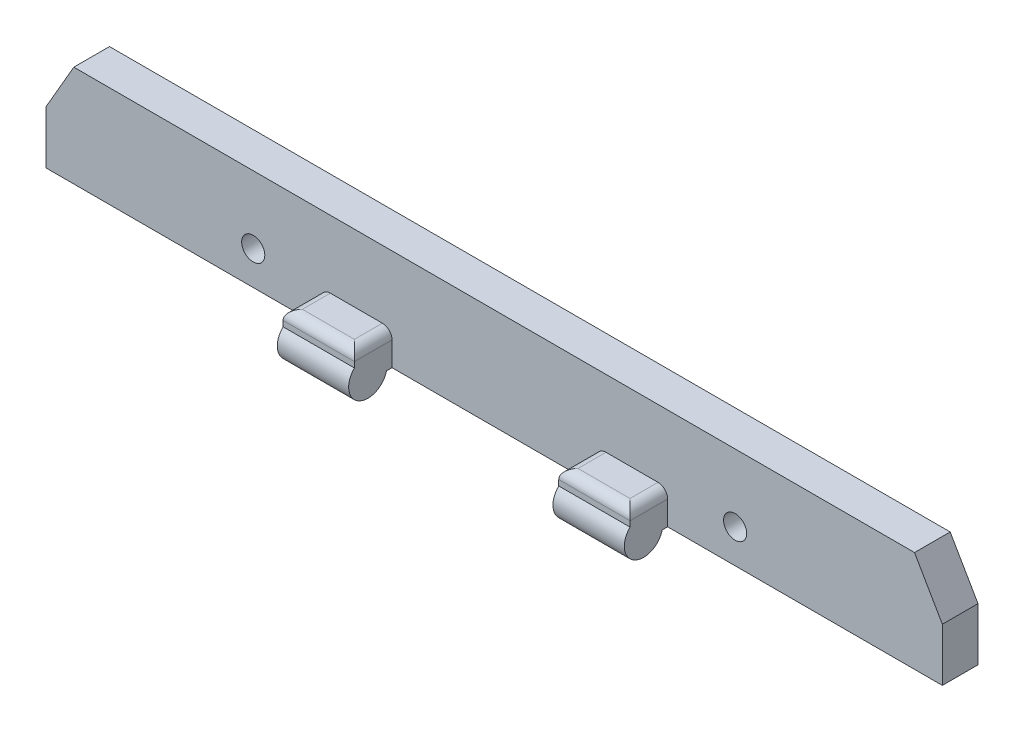
SolidWorks part; units mm, degrees
material "ABS"
ref_plane "正面" through (0, 0, 0) normal (0, 0, 1) x (1, 0, 0)
ref_plane "平面" through (0, 0, 0) normal (0, 1, 0) x (1, 0, 0)
ref_plane "右側面" through (0, 0, 0) normal (1, 0, 0) x (0, 0, -1)
sketch "ｽｹｯﾁ1" plane through (0, 0, 0) normal (0, 0, 1) x (1, 0, 0)
  line L0 (-46.5, 0) -> (46.5, 0) construction
  line L1 (46.5, -3.5) -> (-46.5, -3.5)
  line L2 (46.5, -3.5) -> (46.5, 3.5)
  line L3 (46.5, 3.5) -> (-46.5, 3.5)
  line L4 (-46.5, -3.5) -> (-46.5, 3.5)
  line L5 (46.5, -3.5) -> (-46.5, 3.5) construction
  line L6 (46.5, 3.5) -> (-46.5, -3.5) construction
  circle A0 centre (-25, 0) radius 1.2
  circle A1 centre (25, 0) radius 1.2
  point P0 (0, 0)
  dimension "D4" = 50
  dimension "D5" = 2.4
  dimension "D6" = 2.4
  dimension "D1" = 7
  dimension "D2" = 93
  dimension "D3" = 25
extrude "ﾎﾞｽ - 押し出し1" add sketch "ｽｹｯﾁ1" along normal blind 3.7
sketch "ｽｹｯﾁ2" plane through (0, 0, 3.7) normal (0, 0, 1) x (1, 0, 0)
  line L0 (0, 3.5) -> (0, -3.5) construction
  line L1 (-10.6, -3.5) -> (-18, -3.5)
  line L2 (-10.6, -3.5) -> (-10.6, 0)
  line L3 (-10.6, 0) -> (-18, 0)
  line L4 (-18, -3.5) -> (-18, 0)
  line L5 (-10.6, -3.5) -> (-18, 0) construction
  line L6 (-10.6, 0) -> (-18, -3.5) construction
  line L7 (18, -3.5) -> (10.6, -3.5)
  line L8 (18, -3.5) -> (18, 0)
  line L9 (18, 0) -> (10.6, 0)
  line L10 (10.6, -3.5) -> (10.6, 0)
  line L11 (18, -3.5) -> (10.6, 0) construction
  line L12 (18, 0) -> (10.6, -3.5) construction
  line L13 (46.5, 3.5) -> (-46.5, 3.5) construction
  line L14 (-46.5, -3.5) -> (46.5, -3.5) construction
  line L15 (-46.5, 0) -> (46.5, 0) construction
  line L16 (-46.5, 3.5) -> (-46.5, -3.5) construction
  line L17 (46.5, -3.5) -> (46.5, 3.5) construction
  point P0 (-14.3, -1.75)
  point P5 (14.3, -1.75)
  dimension "D1" = 18
  dimension "D2" = 7.4
  dimension "D3" = 7.4
  dimension "D4" = 18
extrude "ﾎﾞｽ - 押し出し2" add sketch "ｽｹｯﾁ2" along normal blind 5
sketch "ｽｹｯﾁ3" plane through (-18, 0, 0) normal (-1, 0, 0) x (0, 0, 1)
  line L0 (6.2, 0) -> (6.2, -3.5) construction
  line L1 (4.2635, -3.5) -> (8.1365, -3.5)
  line L3 (8.7, 0) -> (3.7, 0) construction
  line L4 (8.7, -3.5) -> (3.7, -3.5) construction
  arc A0 (4.2635, -3.5) -> (8.1365, -3.5) centre (6.2, -3) ccw
  dimension "D1" = 2
  dimension "D2" = 0.5
extrude "ﾎﾞｽ - 押し出し3" add sketch "ｽｹｯﾁ3" against normal up to surface (7.4 mm away) up to face at (-10.6, -1.75, 6.2)
sketch "ｽｹｯﾁ4" plane through (18, 0, 0) normal (1, 0, 0) x (0, 0, -1)
  line L0 (-6.2, 0) -> (-6.2, -3.5) construction
  line L1 (-8.7, 0) -> (-3.7, 0) construction
  line L2 (-8.7, -3.5) -> (-3.7, -3.5) construction
  line L3 (-8.1365, -3.5) -> (-4.2635, -3.5)
  arc A0 (-8.1365, -3.5) -> (-4.2635, -3.5) centre (-6.2, -3) ccw
  dimension "D1" = 2
  dimension "D2" = 0.5
extrude "ﾎﾞｽ - 押し出し4" add sketch "ｽｹｯﾁ4" against normal up to surface (7.4 mm away) up to face at (10.6, -1.75, 6.2)
sketch "ｽｹｯﾁ5" plane through (0, 0, 3.7) normal (0, 0, 1) x (1, 0, 0)
  line L0 (-46.5, 2) -> (-45.634, 3.5)
  line L1 (-46.5, 3.5) -> (-46.5, -3.5) construction
  line L2 (46.5, 3.5) -> (-46.5, 3.5) construction
  line L3 (-45.634, 3.5) -> (-46.5, 3.5)
  line L4 (-46.5, 3.5) -> (-46.5, 2)
  line L5 (-46.5, -3.5) -> (-18, -3.5) construction
  line L6 (0, 3.5) -> (0, -3.5) construction
  line L7 (-10.6, -3.5) -> (10.6, -3.5) construction
  line L8 (46.5, 3.5) -> (46.5, 2)
  line L9 (45.634, 3.5) -> (46.5, 3.5)
  line L10 (46.5, 2) -> (45.634, 3.5)
  dimension "D1" = 5.5
  dimension "D2" = 150
extrude "ｶｯﾄ - 押し出し1" cut sketch "ｽｹｯﾁ5" against normal through all
sketch "ｽｹｯﾁ6" plane through (0, 0, 3.7) normal (0, 0, 1) x (1, 0, 0)
  line L0 (-45.634, 3.5) -> (45.634, 3.5)
  line L1 (45.634, 3.5) -> (43.6132, 7)
  line L2 (43.6132, 7) -> (-43.6132, 7)
  line L3 (-43.6132, 7) -> (-45.634, 3.5)
  dimension "D1" = 60
  dimension "D2" = 3.5
  dimension "D3" = 60
extrude "ﾎﾞｽ - 押し出し5" add sketch "ｽｹｯﾁ6" against normal up to surface (3.7 mm away) up to face at (0, 0.6667, 0)
sketch "ｽｹｯﾁ7" plane through (18, 0, 0) normal (1, 0, 0) x (0, 0, -1)
  line L0 (-7.6013, -1.5729) -> (-6.2, -3) construction
  line L1 (-6.2, -3) -> (-8.1365, -3.5) construction
  line L2 (-7.6013, -1.5729) -> (-7.6013, 0)
  line L3 (-8.7, 0) -> (-3.7, 0) construction
  line L4 (-7.6013, 0) -> (-8.7, 0)
  line L5 (-8.7, 0) -> (-8.7, -3.5)
  line L6 (-8.7, -3.5) -> (-8.1365, -3.5)
  arc A0 (-8.1365, -3.5) -> (-7.6013, -1.5729) centre (-6.2, -3) cw
  dimension "D1" = 60
extrude "ｶｯﾄ - 押し出し2" cut sketch "ｽｹｯﾁ7" against normal through all
fillet "ﾌｨﾚｯﾄ1" radius 1 6 edges at (-18, 0, 5.6506) (10.6, 0, 5.6506) (18, 0, 5.6506) (-10.6, 0, 5.6506) (-14.3, 0, 7.6013) (14.3, 0, 7.6013)
